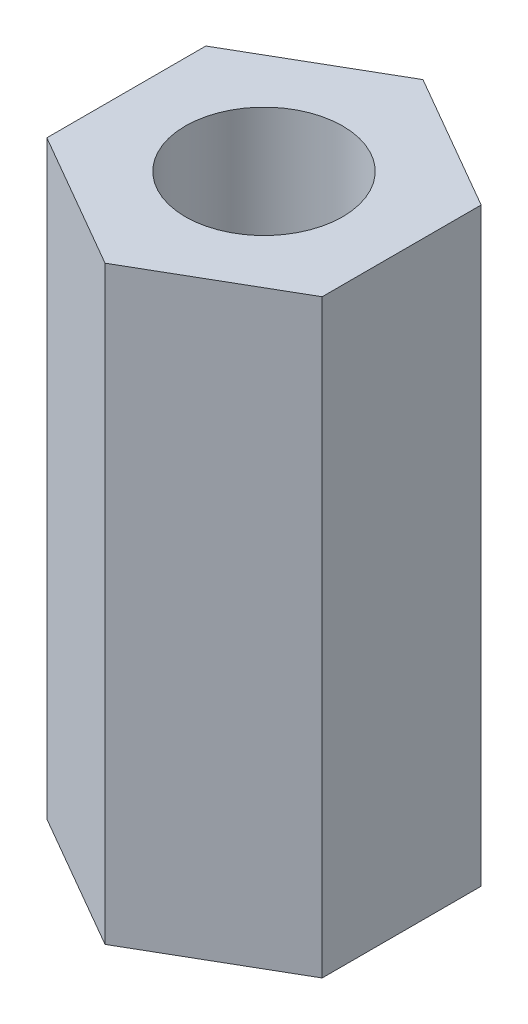
SolidWorks part; units mm, degrees
ref_plane "Ön Düzlem" through (0, 0, 0) normal (0, 0, 1) x (1, 0, 0)
ref_plane "Üst Düzlem" through (0, 0, 0) normal (0, 1, 0) x (1, 0, 0)
ref_plane "Sağ Düzlem" through (0, 0, 0) normal (1, 0, 0) x (0, 0, -1)
sketch "Çizim1" plane through (0, 0, 0) normal (0, 1, 0) x (1, 0, 0)
  line L1 (3.5, 2.0207) -> (0, 4.0415)
  line L2 (0, 4.0415) -> (-3.5, 2.0207)
  line L3 (-3.5, 2.0207) -> (-3.5, -2.0207)
  line L4 (-3.5, -2.0207) -> (0, -4.0415)
  line L5 (0, -4.0415) -> (3.5, -2.0207)
  line L6 (3.5, -2.0207) -> (3.5, 2.0207)
  circle A0 centre (0, 0) radius 3.5 construction
  circle A1 centre (0, 0) radius 2
  dimension "D1" = 4
  dimension "D2" = 7
extrude "Yükseklik-Ekstrüzyon1" add sketch "Çizim1" along normal blind 15
